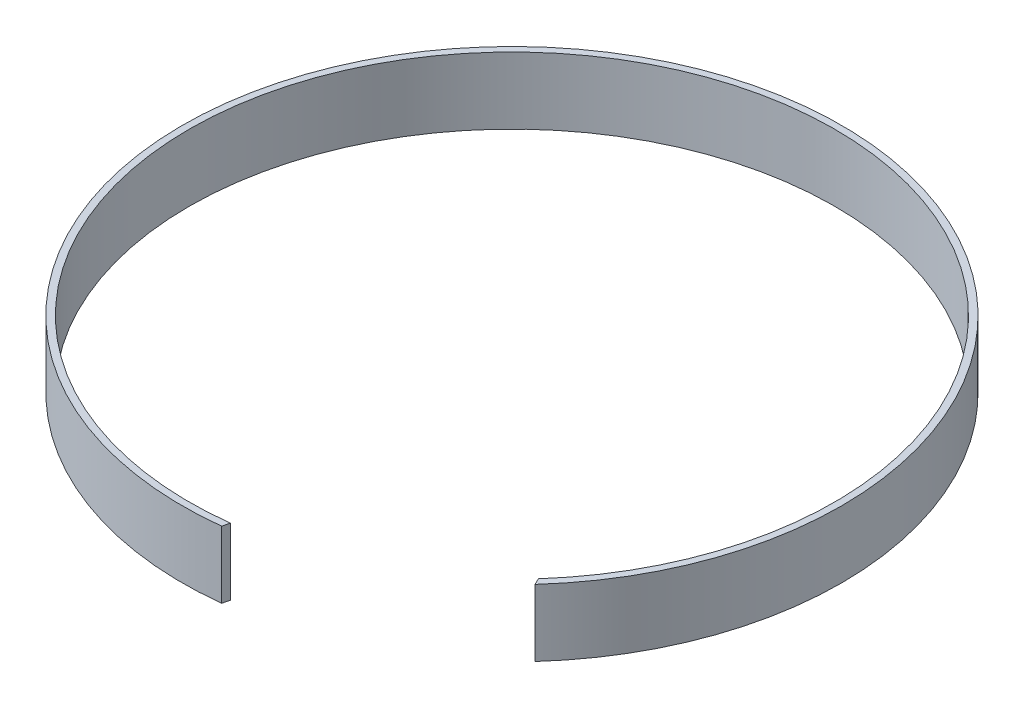
SolidWorks part; units mm, degrees
ref_plane "Front Plane" through (0, 0, 0) normal (0, 0, 1) x (1, 0, 0)
ref_plane "Top Plane" through (0, 0, 0) normal (0, 1, 0) x (1, 0, 0)
ref_plane "Right Plane" through (0, 0, 0) normal (1, 0, 0) x (0, 0, -1)
sketch "Sketch1" plane through (0, 0, 0) normal (0, 1, 0) x (1, 0, 0)
  line L0 (17.4688, -143.9439) -> (16.7383, -147.0836)
  line L1 (109.7096, -99.3859) -> (108.3114, -96.4035)
  arc A0 (109.7096, -99.3859) -> (16.7383, -147.0836) centre (0, 0) ccw
  arc A1 (108.3114, -96.4035) -> (17.4688, -143.9439) centre (0, 0) ccw
extrude "Boss-Extrude1" add sketch "Sketch1" along normal blind 30
